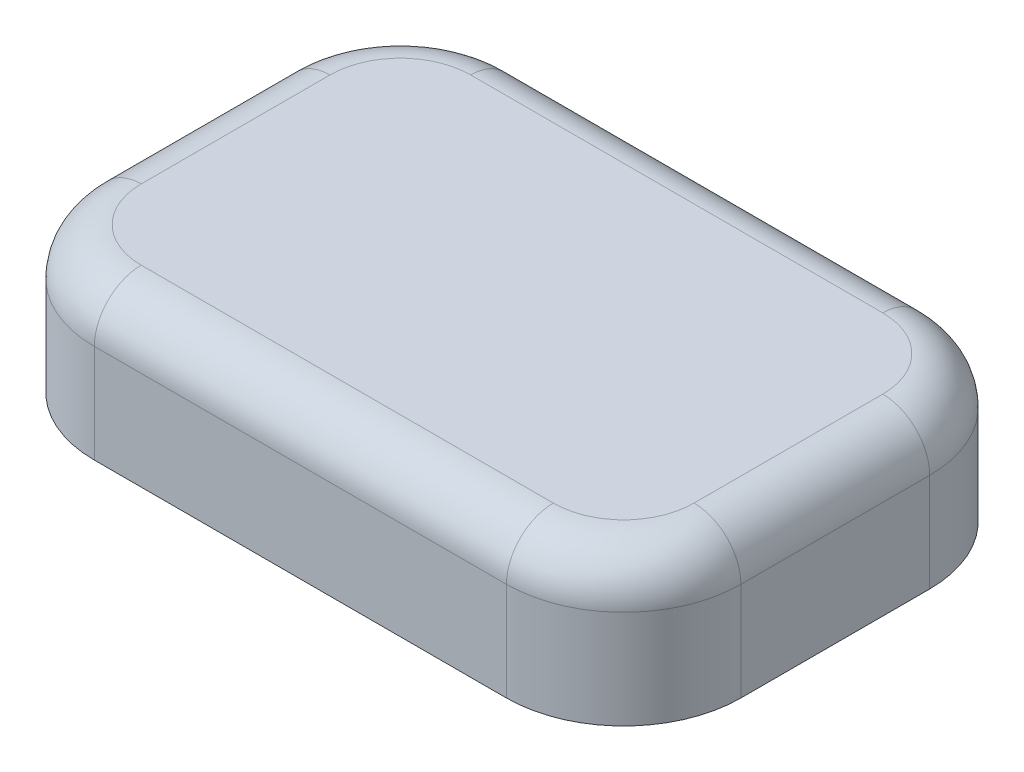
SolidWorks part; units mm, degrees
ref_plane "前视基准面" through (0, 0, 0) normal (0, 0, 1) x (1, 0, 0)
ref_plane "上视基准面" through (0, 0, 0) normal (0, 1, 0) x (1, 0, 0)
ref_plane "右视基准面" through (0, 0, 0) normal (1, 0, 0) x (0, 0, -1)
other "Configuration Table"
sketch "草图1" plane through (0, 0, 0) normal (0, 1, 0) x (1, 0, 0)
  line L0 (-2.2, 0) -> (2.2, 0) construction
  line L1 (0, 2.2) -> (0, -2.2) construction
  line L2 (2.2, 0.6) -> (2.2, -0.6)
  line L3 (-0.6, 2.2) -> (0.6, 2.2)
  line L4 (-2.2, -0.6) -> (-2.2, 0.6)
  line L5 (-0.6, -2.2) -> (0.6, -2.2)
  line L6 (-0.6, 2.2) -> (-0.6, 0.6)
  line L7 (-0.6, 0.6) -> (-2.2, 0.6)
  line L8 (-2.2, -0.6) -> (-0.6, -0.6)
  line L9 (-0.6, -0.6) -> (-0.6, -2.2)
  line L10 (0.6, -2.2) -> (0.6, -0.6)
  line L11 (0.6, -0.6) -> (2.2, -0.6)
  line L12 (2.2, 0.6) -> (0.6, 0.6)
  line L13 (0.6, 0.6) -> (0.6, 2.2)
  circle A0 centre (0, 0) radius 2.8
  point P4 (0, 0)
  point P7 (0, 0)
  point P10 (2.2, 0)
  point P13 (0, 2.2)
  point P16 (-2.2, 0)
  point P19 (0, -2.2)
  dimension "D7" = 5.6
  dimension "D1" = 4.4
  dimension "D2" = 4.4
  dimension "D3" = 1.2
  dimension "D4" = 1.2
  dimension "D5" = 1.2
  dimension "D6" = 1.2
extrude "凸台-拉伸1" add sketch "草图1" against normal blind 5
sketch "草图2" plane through (0, 0, 0) normal (0, 1, 0) x (1, 0, 0)
  line L0 (0, -9.025) -> (0, 9.025) construction
  line L1 (-13.7875, 9.025) -> (13.7875, 9.025)
  line L2 (-13.7875, -9.025) -> (13.7875, -9.025)
  line L3 (-13.7875, 9.025) -> (-13.7875, -9.025)
  line L4 (13.7875, 9.025) -> (13.7875, -9.025)
  point P4 (0, 0)
  point P8 (0, 9.025)
  point P11 (0, -9.025)
  dimension "D1" = 18.05
  dimension "D2" = 27.575
extrude "凸台-拉伸2" add sketch "草图2" along normal blind 1.2
sketch "草图3" plane through (0, 0, 0) normal (0, 1, 0) x (1, 0, 0)
  line L4 (13.7875, -9.025) -> (13.7875, 9.025)
  line L5 (-13.7875, -9.025) -> (13.7875, -9.025)
  line L6 (-13.7875, 9.025) -> (-13.7875, -9.025)
  line L7 (13.7875, 9.025) -> (-13.7875, 9.025)
  line L8 (13.7875, -9.025) -> (13.7875, 9.025)
  line L9 (-13.7875, -9.025) -> (13.7875, -9.025)
  line L10 (-13.7875, 9.025) -> (-13.7875, -9.025)
  line L11 (13.7875, 9.025) -> (-13.7875, 9.025)
  line L20 (12.5875, -7.825) -> (12.5875, 7.825)
  line L21 (12.5875, 7.825) -> (-12.5875, 7.825)
  line L22 (-12.5875, 7.825) -> (-12.5875, -7.825)
  line L23 (-12.5875, -7.825) -> (12.5875, -7.825)
  line L24 (12.5875, -7.825) -> (12.5875, 7.825)
  line L25 (12.5875, 7.825) -> (-12.5875, 7.825)
  line L26 (-12.5875, 7.825) -> (-12.5875, -7.825)
  line L27 (-12.5875, -7.825) -> (12.5875, -7.825)
  dimension "D1" = 0
  dimension "D2" = 1.2
extrude "凸台-拉伸3" add sketch "草图3" against normal blind 5
fillet "圆角1" radius 5 8 edges at (13.7875, -1.9, -9.025) (13.7875, -1.9, 9.025) (-13.7875, -1.9, 9.025) (-13.7875, -1.9, -9.025) (-12.5875, -2.5, -7.825) (12.5875, -2.5, -7.825) (12.5875, -2.5, 7.825) (-12.5875, -2.5, 7.825)
fillet "圆角2" radius 2 16 edges at (12.5875, 0, 0) (0, 0, 7.825) (-12.5875, 0, 0) (0, 0, -7.825) (12.323, 1.2, 7.5605) (0, 1.2, 9.025) (-12.323, 1.2, 7.5605) (-13.7875, 1.2, 0) (-12.323, 1.2, -7.5605) (0, 1.2, -9.025) (12.323, 1.2, -7.5605) (13.7875, 1.2, 0) (11.123, 0, 6.3605) (-11.123, 0, 6.3605) (-11.123, 0, -6.3605) (11.123, 0, -6.3605)
chamfer "倒角1" distance 0.5 angle 45 1 edges at (0, 0, 2.8)
